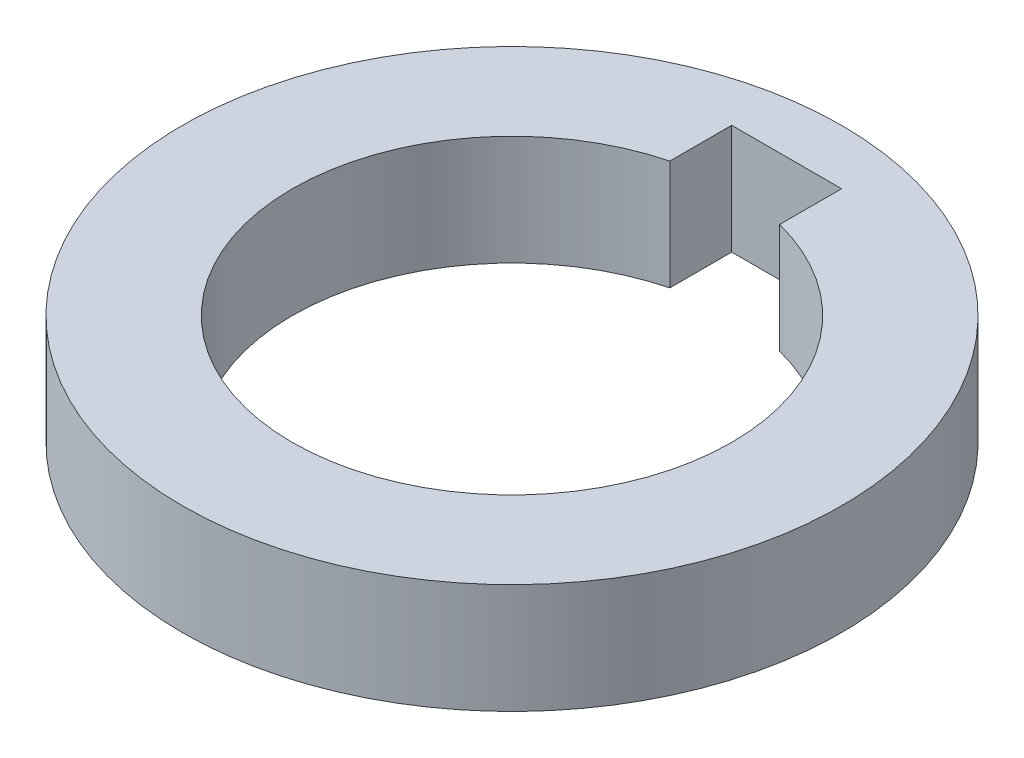
SolidWorks part; units mm, degrees
ref_plane "Front Plane" through (0, 0, 0) normal (0, 0, 1) x (1, 0, 0)
ref_plane "Top Plane" through (0, 0, 0) normal (0, 1, 0) x (1, 0, 0)
ref_plane "Right Plane" through (0, 0, 0) normal (1, 0, 0) x (0, 0, -1)
sketch "Sketch1" plane through (0, 0, 0) normal (0, 1, 0) x (1, 0, 0)
  line L1 (-1.5875, 7.9375) -> (1.5875, 7.9375)
  line L2 (-1.5875, 7.9375) -> (-1.5875, -7.9375)
  line L3 (-1.5875, -7.9375) -> (1.5875, -7.9375)
  line L4 (1.5875, 7.9375) -> (1.5875, -7.9375)
  line L5 (-1.5875, 7.9375) -> (1.5875, -7.9375) construction
  line L6 (-1.5875, -7.9375) -> (1.5875, 7.9375) construction
  circle A0 centre (0, 0) radius 6.35
  circle A1 centre (0, 0) radius 9.525
extrude "Boss-Extrude1" add sketch "Sketch1" along normal blind 3.175 contours A1 A0 L4 L3 L2 L1 | A0 L2 L3 L4
